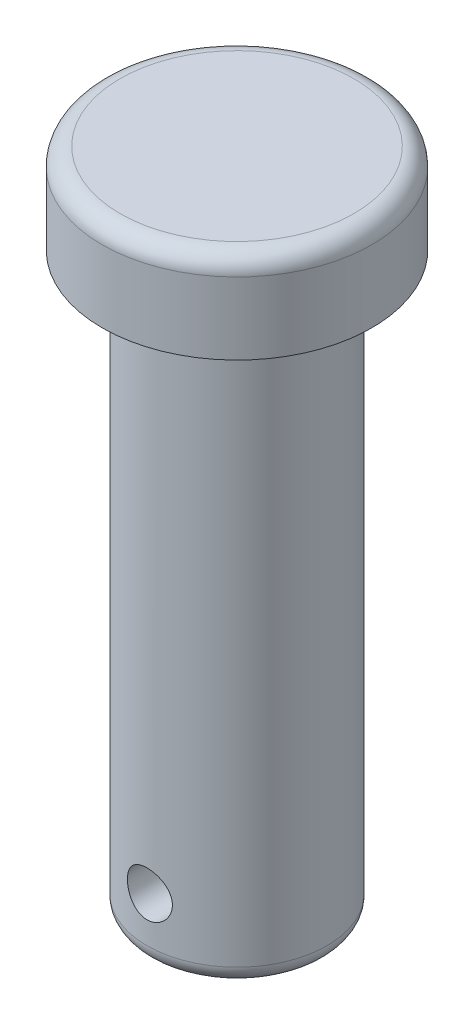
SolidWorks part; units mm, degrees
material "AISI 1045 Steel, cold drawn"
ref_plane "Front Plane" through (0, 0, 0) normal (0, 0, 1) x (1, 0, 0)
ref_plane "Top Plane" through (0, 0, 0) normal (0, 1, 0) x (1, 0, 0)
ref_plane "Right Plane" through (0, 0, 0) normal (1, 0, 0) x (0, 0, -1)
sketch "Sketch1" plane through (0, 0, 0) normal (0, 1, 0) x (1, 0, 0)
  circle A0 centre (0, 0) radius 10
  dimension "D1" = 20
extrude "Boss-Extrude1" add sketch "Sketch1" along normal blind 64 contours A0
sketch "Sketch2" plane through (0, 64, 0) normal (0, 1, 0) x (1, 0, 0)
  circle A0 centre (0, 0) radius 15
  dimension "D1" = 30
extrude "Boss-Extrude2" add sketch "Sketch2" along normal blind 10
sketch "Sketch3" plane through (0, 0, 0) normal (0, 0, 1) x (1, 0, 0)
  line L0 (-10, 0) -> (10, 0) construction
  circle A0 centre (0, 7) radius 2.5
  dimension "D1" = 5
  dimension "D2" = 7
extrude "Cut-Extrude1" cut sketch "Sketch3" against normal through all both and the other way through all
fillet "Fillet1" radius 2 2 edges at (0, 74, 15) (0, 0, 10)
